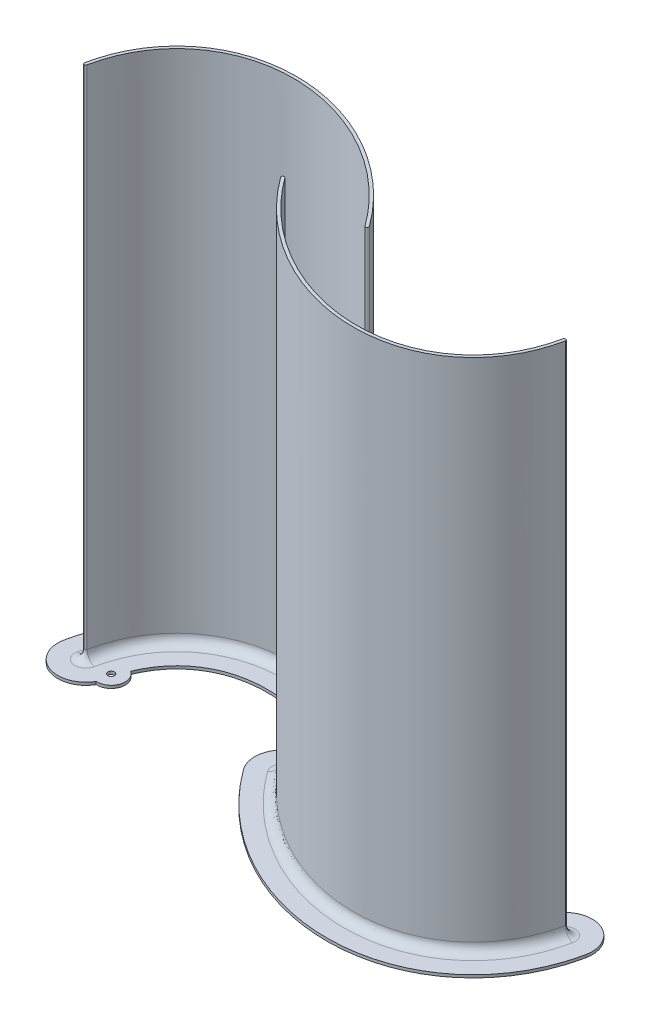
SolidWorks part; units mm, degrees
ref_plane "Front Plane" through (0, 0, 0) normal (0, 0, 1) x (1, 0, 0)
ref_plane "Top Plane" through (0, 0, 0) normal (0, 1, 0) x (1, 0, 0)
ref_plane "Right Plane" through (0, 0, 0) normal (1, 0, 0) x (0, 0, -1)
sketch "Axis" plane through (0, 0, 0) normal (0, 0, 1) x (1, 0, 0)
  line L0 (0, 0) -> (0, 50000) construction
sketch "Geometry" plane through (0, 0, 0) normal (0, 1, 0) x (1, 0, 0)
  line L2 (-218.1299, 67.1512) -> (-84.363, -78.8297) construction
  line L3 (-84.363, -78.8297) -> (26.4387, 22.7014) construction
  line L4 (-255, 0) -> (45, 0) construction
  circle A0 centre (0, 0) radius 255 construction
  ellipse E0 centre (-84.363, -78.8297) end of major axis (49.4038, -224.8106) minor radius 150.285 construction
  point P5 (0, 0)
  point P8 (0, 0)
  point P17 (-156.5971, 0)
  dimension "D1" = 510
  dimension "D6" = 300
  dimension "D5" = 198
  dimension "D2" = 106.92
  dimension "D4" = 150.285
  dimension "D7" = 45
  dimension "D3" = 47.5
sketch "Blade Profile" plane through (0, 0, 0) normal (0, 1, 0) x (1, 0, 0)
  line L0 (-255, 0) -> (45, 0) construction
  arc A0 (46.3344, 0.9704) -> (43.6656, -0.9704) centre (45, 0) cw
  arc A1 (-256.6168, 0.3293) -> (-253.3832, -0.3293) centre (-255, 0) ccw
  ellipse E0 centre (-84.363, -78.8297) end of major axis (-218.1299, 67.1512) minor radius 150.285 (45, 0) -> (-255, 0) ccw construction
  spline S0 degree 1 poles (46.3344, 0.9704) (-256.6168, 0.3293) knots 0 0 1 1 construction
  spline S1 degree 3 poles (46.3344, 0.9704) (43.6286, 4.6912) (38.0232, 11.9832) (26.0128, 26.008) (3.0969, 48.8387) (-34.1692, 75.6316) (-82.7489, 95.9834) (-131.5042, 102.9657) (-169.1835, 97.1438) (-195.8149, 85.7497) (-213.6414, 74.0114) (-228.964, 59.306) (-239.3926, 44.8239) (-246.2103, 32.075) (-250.5372, 21.9812) (-253.4716, 13.163) (-255.4062, 5.901) (-256.2384, 2.1874) (-256.6168, 0.3293) knots -1.719204 -1.719204 -1.719204 -1.719204 -1.649736 -1.580267 -1.44133 -1.163455 -0.88558 -0.607706 -0.329831 -0.190894 -0.051956 0.086981 0.225919 0.295387 0.364856 0.434325 0.469059 0.503793 0.503793 0.503793 0.503793
  spline S2 degree 1 poles (43.6656, -0.9704) (-253.3832, -0.3293) knots 0 0 1 1 construction
  spline S3 degree 3 poles (43.6656, -0.9704) (40.994, 2.7032) (35.4599, 9.9024) (23.6004, 23.751) (0.9724, 46.2949) (-35.8112, 72.7374) (-83.67, 92.7783) (-131.5313, 99.6176) (-168.3302, 93.9167) (-194.2495, 82.8245) (-211.5728, 71.4165) (-226.4563, 57.1327) (-236.5947, 43.0554) (-243.2314, 30.6457) (-247.4479, 20.8101) (-250.311, 12.2069) (-252.2001, 5.1159) (-253.0134, 1.4864) (-253.3832, -0.3293) knots -1.719204 -1.719204 -1.719204 -1.719204 -1.649736 -1.580267 -1.44133 -1.163455 -0.88558 -0.607706 -0.329831 -0.190894 -0.051956 0.086981 0.225919 0.295387 0.364856 0.434325 0.469059 0.503793 0.503793 0.503793 0.503793
  dimension "D1" = 3.3
sketch "Base profile" plane through (0, 0, 0) normal (0, 1, 0) x (1, 0, 0)
  line L0 (228.0351, 0) -> (-228.0351, 0) construction
  arc A0 (69.2625, 17.6445) -> (20.7375, -17.6445) centre (45, 0) cw
  arc A1 (-284.3966, 5.9866) -> (-225.6034, -5.9866) centre (-255, 0) ccw
  circle A2 centre (0, 0) radius 45
  circle A3 centre (-228.0351, 0) radius 15
  ellipse E0 centre (-84.363, -78.8297) end of major axis (-218.1299, 67.1512) minor radius 150.285 (45, 0) -> (-255, 0) ccw construction
  ellipse E1 centre (-84.363, -78.8297) end of major axis (-218.1299, 67.1512) minor radius 150.285 construction
  spline S0 degree 1 poles (69.2625, 17.6445) (-284.3966, 5.9866) knots 0 0 1 1 construction
  spline S1 degree 3 poles (69.2625, 17.6445) (57.2693, 34.1361) (29.6332, 64.7311) (-20.0641, 100.4957) (-74.836, 123.518) (-131.2714, 131.7282) (-176.5145, 124.867) (-209.2626, 110.8796) (-231.4128, 96.3043) (-250.5076, 77.9772) (-263.4292, 60.0169) (-271.8018, 44.3549) (-277.0779, 32.0395) (-281.3318, 19.2546) (-283.4932, 10.4226) (-284.3966, 5.9866) knots -1.719204 -1.719204 -1.719204 -1.719204 -1.44133 -1.163455 -0.88558 -0.607706 -0.329831 -0.190894 -0.051956 0.086981 0.225919 0.295387 0.364856 0.434325 0.503793 0.503793 0.503793 0.503793
  spline S2 degree 1 poles (20.7375, -17.6445) (-225.6034, -5.9866) knots 0 0 1 1 construction
  spline S3 degree 3 poles (20.7375, -17.6445) (18.3606, -14.3761) (13.4388, -7.9733) (2.8759, 4.3615) (-17.2786, 24.4412) (-49.9171, 47.8734) (-91.5827, 65.2437) (-131.764, 70.8552) (-160.9991, 66.1934) (-180.8018, 57.6946) (-193.8014, 49.1235) (-204.9127, 38.4616) (-212.5582, 27.862) (-217.6396, 18.3665) (-220.9079, 10.7488) (-223.158, 3.9933) (-224.6564, -1.629) (-225.308, -4.536) (-225.6034, -5.9866) knots -1.719204 -1.719204 -1.719204 -1.719204 -1.649736 -1.580267 -1.44133 -1.163455 -0.88558 -0.607706 -0.329831 -0.190894 -0.051956 0.086981 0.225919 0.295387 0.364856 0.434325 0.469059 0.503793 0.503793 0.503793 0.503793
  point P7 (0, 0)
  dimension "D2" = 456.0702
  dimension "D3" = 30
  dimension "D1" = 60
extrude "Blade" add sketch "Blade Profile" along normal blind 550
extrude "Base" add sketch "Base profile" against normal blind 3 contours S1 A1 S3 A0 | A2 | A3
hole_wizard "M6 Clearance Hole1" positions "Sketch1" profile "Sketch2" hole size "M6" standard "ANSI Metric" end condition through all
sketch "Sketch1" plane through (0, 0, 0) normal (0, 1, 0) x (1, 0, 0)
  point P0 (-228.0351, 0)
sketch "Sketch2" plane through (-228.0351, 0, 0) normal (1, 0, 0) x (0, 0, 1)
  line L0 (0, 0) -> (0, 3)
  line L1 (0, 3) -> (3.5, 3)
  line L2 (3.5, 3) -> (3.5, 0)
  line L5 (3.5, 0) -> (0, 0)
  line L11 (0, -6.35) -> (0, 107.95) construction
  dimension "Thru Hole Dia." = 7
  dimension "Thru Hole Depth" = 3
fillet "Support" radius 10 4 edges at (-255.3293, 0, 1.6168) (45.9704, 0, 1.3344)
pattern_circular "Blade 2" count 2 over 360 about axis through (0, 0, 0) along (0, 1, 0) of bodies 105 102
combine bodies "Savonious" bodies to combine 105 103
equation "\"elli_mayor\"= 198mm"
equation "\"superposition\"= 30"
equation "\"cut_angle\"= 47.5deg"
equation "\"D3@Geometry\"=\"cut_angle\""
equation "\"D5@Geometry\"=\"elli_mayor\""
equation "\"D2@Geometry\" = 0.54 * \"D5@Geometry\""
equation "\"D7@Geometry\"= \"D6@Geometry\" * \"superposition\" / 200"
